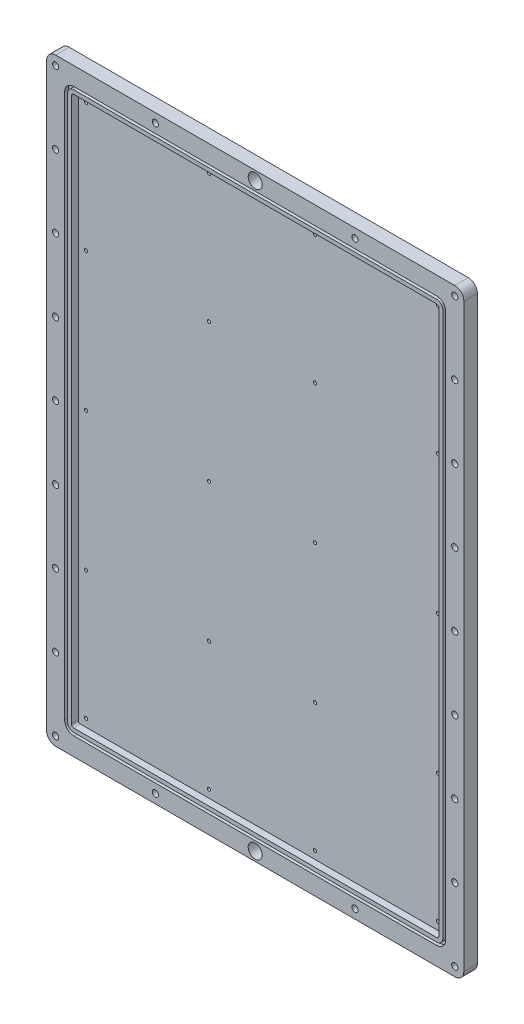
SolidWorks part; units mm, degrees
ref_plane "Front Plane" through (0, 0, 0) normal (0, 0, 1) x (1, 0, 0)
ref_plane "Top Plane" through (0, 0, 0) normal (0, 1, 0) x (1, 0, 0)
ref_plane "Right Plane" through (0, 0, 0) normal (1, 0, 0) x (0, 0, -1)
sketch "Sketch1" plane through (0, 0, 0) normal (0, 0, 1) x (1, 0, 0)
  line L1 (0, 0) -> (292.0492, 0)
  line L2 (0, 0) -> (0, 419.0492)
  line L3 (0, 419.0492) -> (292.0492, 419.0492)
  line L4 (292.0492, 0) -> (292.0492, 419.0492)
  dimension "D1" = 419.0492
  dimension "D2" = 292.0492
extrude "Boss-Extrude1" add sketch "Sketch1" along normal blind 9.525
sketch "Sketch4" plane through (0, 0, 9.525) normal (0, 0, 1) x (1, 0, 0)
  line L0 (91.477, 6.3246) -> (91.477, 0) construction
  line L1 (0, 0) -> (292.0492, 0) construction
  line L2 (6.3246, 94.9672) -> (0, 94.9672) construction
  line L4 (6.3246, 412.7246) -> (285.7246, 412.7246) construction
  line L5 (6.3246, 412.7246) -> (6.3246, 6.3246) construction
  line L6 (6.3246, 6.3246) -> (285.7246, 6.3246) construction
  line L7 (285.7246, 412.7246) -> (285.7246, 6.3246) construction
  line L11 (0, 419.0492) -> (0, 0) construction
  line L12 (285.7246, 110.613) -> (292.0492, 110.613) construction
  line L13 (292.0492, 0) -> (292.0492, 419.0492) construction
  line L14 (125.5626, 412.7246) -> (125.5626, 419.0492) construction
  line L15 (292.0492, 419.0492) -> (0, 419.0492) construction
  circle A0 centre (6.3246, 6.3246) radius 2.1844
  circle A1 centre (6.3246, 412.7246) radius 2.1844
  circle A2 centre (285.7246, 412.7246) radius 2.1844
  circle A3 centre (285.7246, 6.3246) radius 2.1844
  dimension "D5" = 4.3688
  dimension "D1" = 279.4
  dimension "D2" = 406.4
extrude "Cut-Extrude1" cut sketch "Sketch4" against normal through all
sketch "Sketch5" plane through (0, 0, 9.525) normal (0, 0, 1) x (1, 0, 0)
  line L0 (0, 209.5246) -> (12.6746, 209.5246) construction
  line L1 (19.0246, 406.3746) -> (273.0246, 406.3746)
  line L2 (12.6746, 400.0246) -> (12.6746, 19.0246)
  line L3 (19.0246, 12.6746) -> (273.0246, 12.6746)
  line L4 (279.3746, 400.0246) -> (279.3746, 19.0246)
  line L5 (0, 419.0492) -> (0, 0) construction
  line L6 (279.3746, 209.5246) -> (292.0492, 209.5246) construction
  line L8 (19.0246, 14.7066) -> (273.0246, 14.7066)
  line L9 (14.7066, 400.0246) -> (14.7066, 19.0246)
  line L10 (19.0246, 404.3426) -> (273.0246, 404.3426)
  line L11 (277.3426, 400.0246) -> (277.3426, 19.0246)
  line L12 (292.0492, 0) -> (292.0492, 419.0492) construction
  line L13 (146.0246, 12.6746) -> (146.0246, 0) construction
  line L14 (0, 0) -> (292.0492, 0) construction
  line L15 (146.0246, 406.3746) -> (146.0246, 419.0492) construction
  line L16 (292.0492, 419.0492) -> (0, 419.0492) construction
  arc A0 (273.0246, 12.6746) -> (279.3746, 19.0246) centre (273.0246, 19.0246) ccw
  arc A1 (12.6746, 19.0246) -> (19.0246, 12.6746) centre (19.0246, 19.0246) ccw
  arc A2 (273.0246, 406.3746) -> (279.3746, 400.0246) centre (273.0246, 400.0246) cw
  arc A3 (19.0246, 406.3746) -> (12.6746, 400.0246) centre (19.0246, 400.0246) ccw
  arc A4 (14.7066, 19.0246) -> (19.0246, 14.7066) centre (19.0246, 19.0246) ccw
  arc A5 (19.0246, 404.3426) -> (14.7066, 400.0246) centre (19.0246, 400.0246) ccw
  arc A6 (273.0246, 404.3426) -> (277.3426, 400.0246) centre (273.0246, 400.0246) cw
  arc A7 (273.0246, 14.7066) -> (277.3426, 19.0246) centre (273.0246, 19.0246) ccw
  dimension "D5" = 6.35
  dimension "D1" = 266.7
  dimension "D2" = 393.7
  dimension "D6" = 2.032
  dimension "D7" = 2.032
extrude "Cut-Extrude2" cut sketch "Sketch5" against normal blind 2.54 contours L1 A3 L2 A1 L3 A0 L4 A2 A7 L8 A4 L9 A5 L10 A6 L11
pattern_linear "LPattern3" count 4 spacing 69.85 along (1, 0, 0) of "Cut-Extrude1"
pattern_linear "LPattern4" count 8 spacing 50.8 along (0, -1, 0) of "Cut-Extrude1"
sketch "Sketch6" plane through (0, 0, 9.525) normal (0, 0, 1) x (1, 0, 0)
  line L4 (274.6121, 19.0246) -> (274.6121, 400.0246)
  line L5 (274.6121, 19.0246) -> (274.6121, 400.0246)
  line L6 (273.0246, 401.6121) -> (19.0246, 401.6121)
  line L7 (273.0246, 401.6121) -> (19.0246, 401.6121)
  line L8 (17.4371, 400.0246) -> (17.4371, 19.0246)
  line L9 (17.4371, 400.0246) -> (17.4371, 19.0246)
  line L10 (19.0246, 17.4371) -> (273.0246, 17.4371)
  line L11 (19.0246, 17.4371) -> (273.0246, 17.4371)
  arc A4 (273.0246, 17.4371) -> (274.6121, 19.0246) centre (273.0246, 19.0246) ccw
  arc A5 (273.0246, 17.4371) -> (274.6121, 19.0246) centre (273.0246, 19.0246) ccw
  arc A6 (274.6121, 400.0246) -> (273.0246, 401.6121) centre (273.0246, 400.0246) ccw
  arc A7 (274.6121, 400.0246) -> (273.0246, 401.6121) centre (273.0246, 400.0246) ccw
  arc A8 (19.0246, 401.6121) -> (17.4371, 400.0246) centre (19.0246, 400.0246) ccw
  arc A9 (19.0246, 401.6121) -> (17.4371, 400.0246) centre (19.0246, 400.0246) ccw
  arc A10 (17.4371, 19.0246) -> (19.0246, 17.4371) centre (19.0246, 19.0246) ccw
  arc A11 (17.4371, 19.0246) -> (19.0246, 17.4371) centre (19.0246, 19.0246) ccw
  dimension "D1" = 2.7305
extrude "Cut-Extrude3" cut sketch "Sketch6" against normal blind 4.7625
sketch "Sketch7" plane through (0, 0, 4.7625) normal (0, 0, 1) x (1, 0, 0)
  line L0 (273.0246, 401.6121) -> (19.0246, 401.6121) construction
  line L1 (22.8346, 396.2146) -> (269.2146, 396.2146) construction
  line L2 (22.8346, 396.2146) -> (22.8346, 22.8346) construction
  line L3 (22.8346, 22.8346) -> (269.2146, 22.8346) construction
  line L4 (269.2146, 396.2146) -> (269.2146, 22.8346) construction
  line L5 (17.4371, 400.0246) -> (17.4371, 19.0246) construction
  line L6 (274.6121, 19.0246) -> (274.6121, 400.0246) construction
  line L7 (269.2146, 112.649) -> (22.8346, 112.649) construction
  line L8 (17.4371, 400.0246) -> (17.4371, 19.0246) construction
  line L9 (274.6121, 19.0246) -> (274.6121, 400.0246) construction
  line L10 (269.2146, 209.5246) -> (22.8346, 209.5246) construction
  line L11 (183.1594, 396.2146) -> (183.1594, 22.8346) construction
  line L12 (108.8898, 22.8346) -> (108.8898, 396.2146) construction
  line L13 (269.2146, 306.4002) -> (22.8346, 306.4002) construction
  line L16 (19.0246, 17.4371) -> (273.0246, 17.4371) construction
  circle A0 centre (22.8346, 396.2146) radius 1.1303
  circle A1 centre (269.2146, 396.2146) radius 1.1303
  circle A2 centre (22.8346, 22.8346) radius 1.1303
  circle A3 centre (108.8898, 22.8346) radius 1.1303
  circle A4 centre (108.8898, 396.2146) radius 1.1303
  circle A5 centre (183.1594, 396.2146) radius 1.1303
  circle A6 centre (183.1594, 22.8346) radius 1.1303
  circle A7 centre (269.2146, 22.8346) radius 1.1303
  circle A8 centre (269.2146, 112.649) radius 1.1303
  circle A9 centre (108.8898, 112.649) radius 1.1303
  circle A10 centre (183.1594, 112.649) radius 1.1303
  circle A11 centre (22.8346, 112.649) radius 1.1303
  circle A12 centre (269.2146, 209.5246) radius 1.1303
  circle A13 centre (108.8898, 209.5246) radius 1.1303
  circle A14 centre (183.1594, 209.5246) radius 1.1303
  circle A15 centre (22.8346, 209.5246) radius 1.1303
  circle A16 centre (269.2146, 306.4002) radius 1.1303
  circle A17 centre (108.8898, 306.4002) radius 1.1303
  circle A18 centre (183.1594, 306.4002) radius 1.1303
  circle A19 centre (22.8346, 306.4002) radius 1.1303
  dimension "D5" = 2.2606
  dimension "D11" = 96.8756
  dimension "D9" = 373.38
  dimension "D13" = 86.0552
  dimension "D14" = 86.0552
  dimension "D1" = 5.3975
  dimension "D2" = 5.3975
  dimension "D3" = 5.3975
  dimension "D4" = 5.3975
  dimension "D6" = 91.4527
  dimension "D7" = 91.4527
  dimension "D8" = 91.4527
  dimension "D10" = 96.8756
  dimension "D12" = 91.4527
extrude "Cut-Extrude4" cut sketch "Sketch7" against normal blind 3.175
sketch "Sketch8" plane through (0, 0, 9.525) normal (0, 0, 1) x (1, 0, 0)
  circle A0 centre (146.0246, 412.7246) radius 4.9022
  circle A1 centre (146.0246, 6.3246) radius 4.9022
  dimension "D1" = 9.8044
extrude "Cut-Extrude5" cut sketch "Sketch8" against normal through all
fillet "Fillet1" radius 6.35 4 edges at (292.0492, 0, 4.7625) (0, 0, 4.7625) (292.0492, 419.0492, 4.7625) (0, 419.0492, 4.7625)
chamfer "Chamfer1" distance 2.8448 angle 41 22 edges at (78.359, 412.7246, 0) (218.059, 412.7246, 0) (287.909, 412.7246, 0) (287.909, 361.9246, 0) (287.909, 311.1246, 0) (287.909, 260.3246, 0) (287.909, 209.5246, 0) (287.909, 158.7246, 0) (287.909, 107.9246, 0) (287.909, 57.1246, 0) (287.909, 6.3246, 0) (218.059, 6.3246, 0) (78.359, 6.3246, 0) (8.509, 6.3246, 0) (8.509, 57.1246, 0) (8.509, 107.9246, 0) (8.509, 158.7246, 0) (8.509, 260.3246, 0) (8.509, 311.1246, 0) (8.509, 412.7246, 0) (8.509, 361.9246, 0) (8.509, 209.5246, 0)
